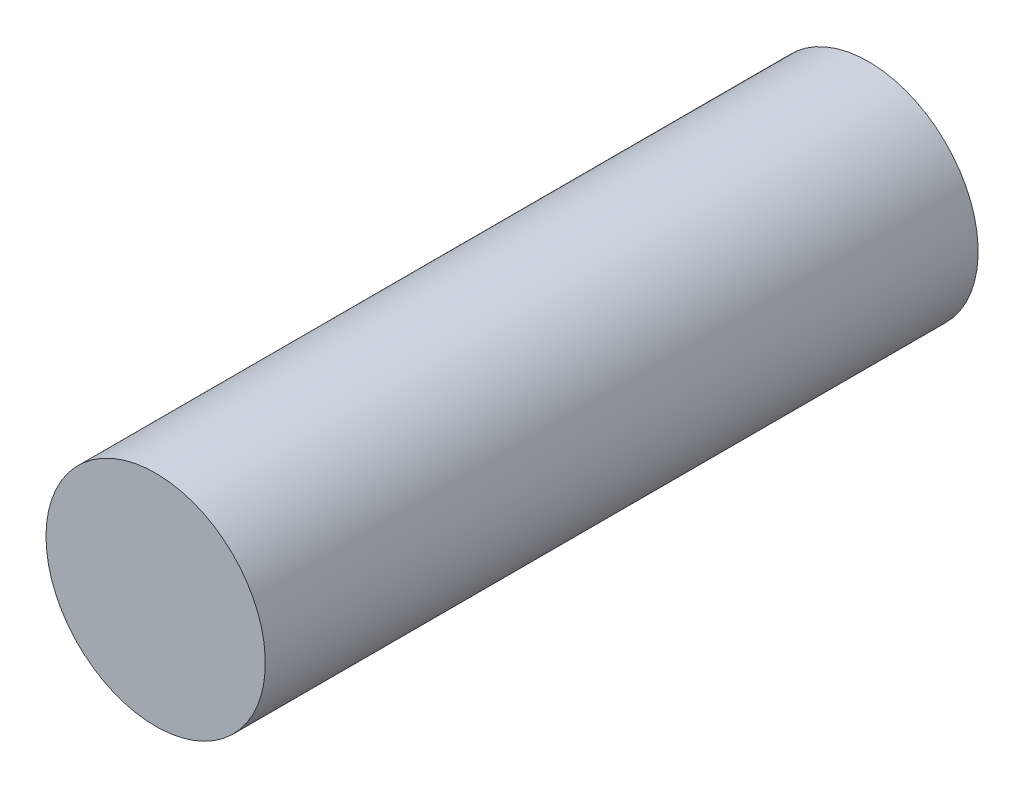
SolidWorks part; units mm, degrees
ref_plane "Front Plane" through (0, 0, 0) normal (0, 0, 1) x (1, 0, 0)
ref_plane "Top Plane" through (0, 0, 0) normal (0, 1, 0) x (1, 0, 0)
ref_plane "Right Plane" through (0, 0, 0) normal (1, 0, 0) x (0, 0, -1)
sketch "Sketch1" plane through (0, 0, 0) normal (0, 0, 1) x (1, 0, 0)
  circle A0 centre (0, 0) radius 8
  dimension "D1" = 16
extrude "Boss-Extrude1" add sketch "Sketch1" along normal mid plane 52
cosmetic thread "Cosmetic Thread1" parameters "D1"=22, "D2"=14.344
cosmetic thread "Cosmetic Thread3" parameters "D1"=15, "D2"=14.344
